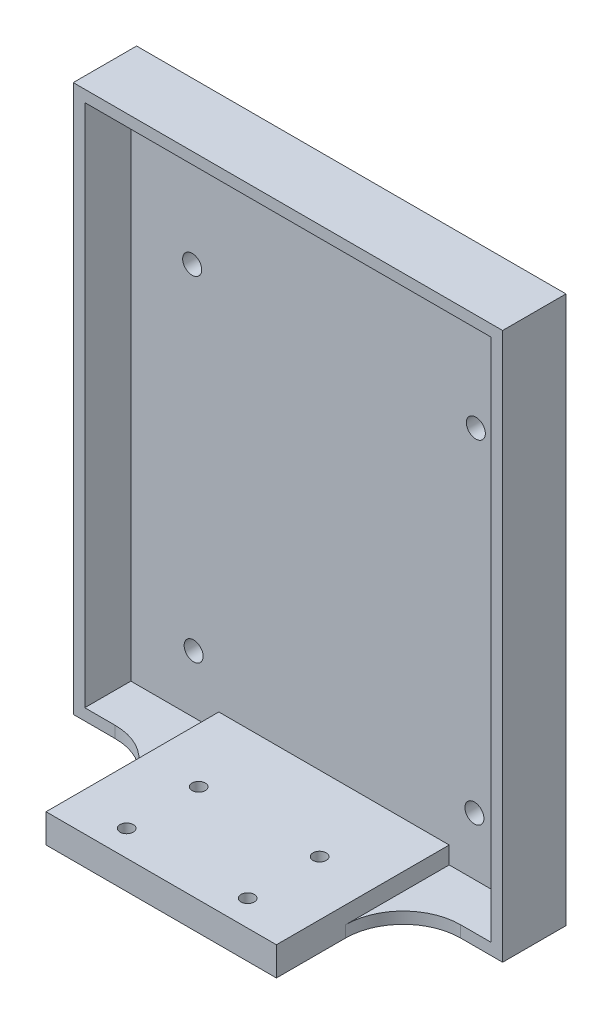
SolidWorks part; units mm, degrees
ref_plane "Alzado" through (0, 0, 0) normal (0, 0, 1) x (1, 0, 0)
ref_plane "Planta" through (0, 0, 0) normal (0, 1, 0) x (1, 0, 0)
ref_plane "Vista lateral" through (0, 0, 0) normal (1, 0, 0) x (0, 0, -1)
sketch "Croquis1" plane through (0, 0, 0) normal (0, 0, 1) x (1, 0, 0)
  line L0 (-55.75, 30) -> (-32.25, 30)
  line L1 (-32.25, 30) -> (-32.25, -30)
  line L2 (-32.25, -30) -> (-55, -34.2202)
  line L3 (-55, -34.2202) -> (-55, -125.7202)
  line L4 (-40.7501, 45) -> (0, 45)
  line L6 (-15, 15) -> (-15, -15)
  line L11 (-55, -125.7202) -> (-37.2737, -140.5944)
  line L12 (40.75, 45) -> (0, 45)
  line L17 (55, -125.7202) -> (37.2737, -140.5944)
  line L20 (15, 15) -> (15, -15)
  line L21 (-55, -79.9702) -> (55, -79.9702) construction
  line L22 (55, -34.2202) -> (55, -125.7202)
  line L23 (32.25, -30) -> (55, -34.2202)
  line L24 (32.25, 30) -> (32.25, -30)
  line L25 (55.75, 30) -> (32.25, 30)
  line L26 (-55.75, -189.9405) -> (-37.2737, -189.9405)
  line L27 (55.75, -189.9405) -> (37.2737, -189.9405)
  line L28 (40.75, -204.9405) -> (0, -204.9405)
  line L29 (-40.7501, -204.9405) -> (0, -204.9405)
  line L30 (-37.2737, -189.9405) -> (-37.2737, -140.5944)
  line L31 (37.2737, -189.9405) -> (37.2737, -140.5944)
  line L32 (-15, 15) -> (15, 15)
  line L33 (-15, -15) -> (15, -15)
  arc A4 (-55.75, 30) -> (-40.7501, 45) centre (-40.75, 30) cw
  arc A5 (55.75, 30) -> (40.75, 45) centre (40.75, 30) ccw
  arc A8 (55.75, -189.9405) -> (40.75, -204.9405) centre (40.75, -189.9405) cw
  arc A9 (-55.75, -189.9405) -> (-40.7501, -204.9405) centre (-40.75, -189.9405) ccw
  point P11 (0, 15)
  point P13 (-15, 0)
  point P20 (-32.25, 0)
  dimension "D10" = 15
  dimension "D22" = 15
  dimension "D1" = 60
  dimension "D3" = 55
  dimension "D4" = 23.5
  dimension "D5" = 91.5
  dimension "D6" = 23.1381
  dimension "D7" = 30
  dimension "D8" = 30
  dimension "D9" = 17.25
  dimension "D11" = 14.9999
  dimension "D12" = 15
  dimension "D13" = 23.14
  dimension "D14" = 18.4763
  dimension "D16" = 130
  dimension "D19" = 15
  dimension "D20" = 110
  dimension "D21" = 23.14
  dimension "D23" = 23.5
  dimension "D24" = 23.1381
extrude "Saliente-Extruir1" add sketch "Croquis1" along normal blind 15
sketch "Croquis6" plane through (-32.25, 0, 0) normal (-1, 0, 0) x (0, 0, 1)
  line L5 (0, 0) -> (5.215, 0) construction
  line L6 (0, 30) -> (0, -30) construction
  circle A0 centre (3, 0) radius 11.175
  circle A1 centre (3, 0) radius 5 construction
  circle A2 centre (3, 0) radius 25 construction
  dimension "D1" = 22.35
  dimension "D3" = 10
  dimension "D4" = 50
  dimension "D2" = 3
extrude "Cortar-Extruir1" cut sketch "Croquis6" against normal blind 10
sketch "Croquis11" plane through (0, 0, 0) normal (0, 0, -1) x (-1, 0, 0)
  line L0 (32.25, -10.7648) -> (32.25, -30) construction
  line L1 (15, 20) -> (32.25, 20)
  line L2 (15, 20) -> (15, -20)
  line L3 (15, -20) -> (32.25, -20)
  line L4 (32.25, 20) -> (32.25, -20)
  line L5 (15, 15) -> (15, -15) construction
  line L6 (55.75, 30) -> (32.25, 30) construction
  line L7 (0, -8.0419) -> (0, 11.3864) construction
  line L8 (-15, -20) -> (-32.25, -20)
  line L9 (-32.25, 20) -> (-32.25, -20)
  line L10 (-15, 20) -> (-32.25, 20)
  line L11 (-15, 20) -> (-15, -20)
  dimension "D1" = 10
  dimension "D2" = 10
extrude "Saliente-Extruir3" add sketch "Croquis11" along normal blind 12
sketch "Croquis9" plane through (-22.25, 0, 0) normal (-1, 0, 0) x (0, 0, 1)
  circle A0 centre (3, 0) radius 5
  arc A1 (0, -10.7648) -> (0, 10.7648) centre (3, 0) ccw construction
  dimension "D1" = 10
extrude "Cortar-Extruir2" cut sketch "Croquis9" against normal through all both and the other way through all
sketch "Croquis12" plane through (32.25, 0, 0) normal (1, 0, 0) x (0, 0, -1)
  line L2 (0, 0) -> (-9.4705, 0) construction
  line L5 (12, 20) -> (12, -20) construction
  line L6 (0, 20) -> (12, 20)
  line L7 (12, 20) -> (12, 5)
  line L8 (12, -20) -> (12, -5)
  line L9 (0, -20) -> (12, -20)
  arc A3 (12, 5) -> (0, 20) centre (-3.375, 5) ccw
  arc A4 (12, -5) -> (0, -20) centre (-3.375, -5) cw
  dimension "D1" = 15
sketch "Croquis14" plane through (0, 0, 15) normal (0, 0, 1) x (1, 0, 0)
  line L0 (-32.25, 30) -> (-32.25, -30) construction
  line L1 (32.25, 41.5932) -> (-32.25, 41.5932)
  line L2 (32.25, 41.5932) -> (32.25, -40.4068)
  line L3 (32.25, -40.4068) -> (-32.25, -40.4068)
  line L4 (-32.25, 41.5932) -> (-32.25, -40.4068)
  line L5 (32.25, -30) -> (32.25, 30) construction
  line L8 (40.75, 45) -> (-40.7501, 45) construction
  dimension "D1" = 3.4068
  dimension "D2" = 10.4068
extrude "Saliente-Extruir4" add sketch "Croquis14" along normal blind 40
sketch "Croquis10" plane through (32.25, 0, 0) normal (1, 0, 0) x (0, 0, -1)
  circle A0 centre (-3, 0) radius 11.175
  circle A1 centre (-3, 0) radius 5 construction
  arc A2 (0, 10.7648) -> (0, -10.7648) centre (-3, 0) ccw construction
extrude "Cortar-Extruir3" cut sketch "Croquis10" against normal blind 10
sketch "Croquis13" plane through (-32.25, 0, 0) normal (-1, 0, 0) x (0, 0, 1)
  circle A0 centre (3, 0) radius 11.175
  arc A1 (0, -10.7648) -> (0, 10.7648) centre (3, 0) ccw construction
extrude "Cortar-Extruir5" cut sketch "Croquis13" against normal blind 10 and the other way through all
sketch "Croquis15" plane through (0, -40.4068, 0) normal (0, -1, 0) x (1, 0, 0)
  line L0 (-22.25, 15) -> (-22.25, 35)
  line L1 (-32.25, 15) -> (32.25, 15) construction
  line L2 (-12.25, 45) -> (12.25, 45)
  line L3 (22.25, 35) -> (22.25, 15)
  line L4 (22.25, 15) -> (-22.25, 15)
  line L5 (-32.25, 55) -> (-32.25, 15) construction
  line L6 (32.25, 55) -> (32.25, 15) construction
  line L7 (-32.25, 55) -> (32.25, 55) construction
  arc A0 (22.25, 35) -> (12.25, 45) centre (12.25, 35) ccw
  arc A1 (-22.25, 35) -> (-12.25, 45) centre (-12.25, 35) cw
  dimension "D4" = 10
  dimension "D1" = 10
  dimension "D2" = 10
  dimension "D3" = 10
extrude "Cortar-Extruir6" cut sketch "Croquis15" against normal through all
sketch "Croquis16" plane through (0, 0, 55) normal (0, 0, 1) x (1, 0, 0)
  line L1 (-28, 38.5) -> (28, 38.5)
  line L2 (-28, 38.5) -> (-28, -38.5)
  line L3 (-28, -38.5) -> (28, -38.5)
  line L4 (28, 38.5) -> (28, -38.5)
  line L5 (-32.25, 41.5932) -> (32.25, 41.5932)
  line L6 (-32.25, 41.5932) -> (-32.25, -40.4068)
  line L7 (-32.25, -40.4068) -> (32.25, -40.4068)
  line L8 (32.25, 41.5932) -> (32.25, -40.4068)
  point P4 (0, 38.5)
  point P6 (28, 0)
  dimension "D1" = 77
  dimension "D2" = 56
extrude "Saliente-Extruir5" add sketch "Croquis16" along normal blind 5
sketch "Croquis17" plane through (0, 0, 15) normal (0, 0, 1) x (1, 0, 0)
  line L0 (15, 15) -> (15, 45)
  line L1 (15, 45) -> (-15, 45)
  line L2 (40.75, 45) -> (-40.7501, 45) construction
  line L3 (-15, 45) -> (-15, 15)
  line L4 (15, 15) -> (-15, 15) construction
  line L5 (15, 15) -> (-15, 15)
  line L6 (-15, 15) -> (-15, -15) construction
extrude "Cortar-Extruir7" cut sketch "Croquis17" against normal through all
sketch "Croquis19" plane through (0, -15, 0) normal (0, 1, 0) x (1, 0, 0)
  line L0 (-15, -15) -> (-15, 0) construction
  line L1 (15, -15) -> (-3, -15)
  line L2 (15, -15) -> (15, -10.5)
  line L3 (15, -10.5) -> (-3, -10.5)
  line L4 (-3, -15) -> (-3, -10.5)
  dimension "D1" = 12
  dimension "D2" = 2.5
extrude "Saliente-Extruir6" add sketch "Croquis19" along normal up to vertex (60 mm away)
sketch "Croquis22" plane through (0, -15, 0) normal (0, 1, 0) x (1, 0, 0)
  line L1 (-15, 0) -> (-3, 0)
  line L2 (-15, 0) -> (-15, -15)
  line L3 (-15, -15) -> (-3, -15)
  line L4 (-3, 0) -> (-3, -15)
extrude "Cortar-Extruir8" cut sketch "Croquis22" against normal blind 2
sketch "Croquis23" plane through (0, 0, 15) normal (0, 0, 1) x (1, 0, 0)
  line L1 (51.2, -56.4702) -> (55, -56.4702)
  line L2 (51.2, -56.4702) -> (51.2, -103.4702)
  line L3 (51.2, -103.4702) -> (55, -103.4702)
  line L4 (55, -56.4702) -> (55, -103.4702)
  line L6 (55, -125.7202) -> (55, -34.2202) construction
  line L7 (0, 0) -> (0, -130.3454) construction
  line L8 (-51.2, -103.4702) -> (-55, -103.4702)
  line L9 (-55, -56.4702) -> (-55, -103.4702)
  line L10 (-51.2, -56.4702) -> (-55, -56.4702)
  line L11 (-51.2, -56.4702) -> (-51.2, -103.4702)
  point P6 (55, -79.9702)
  point P7 (55, -79.9702)
  dimension "D1" = 3.8
  dimension "D2" = 47
extrude "Saliente-Extruir8" add sketch "Croquis23" along normal blind 19.8
sketch "Croquis24" plane through (55, 0, 0) normal (1, 0, 0) x (0, 0, -1)
  line L0 (-34.8, -103.4702) -> (-15, -103.4702) construction
  line L1 (-34.8, -103.4702) -> (-34.8, -56.4702) construction
  line L2 (-34.8, -102.4702) -> (-15, -102.4702) construction
  line L3 (-34.8, -102.4702) -> (-34.8, -57.4702) construction
  line L4 (-34.8, -57.4702) -> (-15, -57.4702) construction
  line L5 (-15, -102.4702) -> (-15, -57.4702) construction
  line L6 (-15, -125.7202) -> (-15, -103.4702) construction
  line L7 (-34.8, -56.4702) -> (-15, -56.4702) construction
  line L8 (-20.1, -85.9702) -> (-15.3, -85.9702)
  line L9 (-20.1, -85.9702) -> (-20.1, -73.9702)
  line L10 (-20.1, -73.9702) -> (-15.3, -73.9702)
  line L11 (-15.3, -85.9702) -> (-15.3, -73.9702)
  line L12 (-24.9, -56.4702) -> (-24.9, -58.3702) construction
  line L13 (-24.9, -103.4702) -> (-24.9, -101.771) construction
  circle A0 centre (-25.3, -66.9702) radius 8.35
  circle A1 centre (-25.3, -92.9702) radius 8.35
  circle A2 centre (-16.3, -101.2702) radius 1
  circle A3 centre (-33.7, -58.3702) radius 1
  circle A4 centre (-16.1, -58.3702) radius 1
  circle A5 centre (-33.5, -101.2702) radius 1
  point P16 (-20.1, -79.9702)
  point P20 (-34.8, -79.9702)
  point P21 (-34.8, -79.9702)
  dimension "D1" = 16.7
  dimension "D2" = 16.7
  dimension "D3" = 2
  dimension "D4" = 2.2
  dimension "D5" = 2
  dimension "D6" = 1.9
  dimension "D7" = 45
  dimension "D8" = 13
  dimension "D9" = 1.3
  dimension "D10" = 1.1
  dimension "D11" = 13
  dimension "D12" = 12
  dimension "D13" = 4.8
  dimension "D14" = 0.3
  dimension "D15" = 9.5
extrude "Cortar-Extruir10" cut sketch "Croquis24" against normal through all
sketch "Croquis25" plane through (0, 0, 34.8) normal (0, 0, 1) x (1, 0, 0)
  line L1 (-55, -56.4702) -> (-51.2, -56.4702)
  line L2 (-55, -56.4702) -> (-55, -103.4702)
  line L3 (-55, -103.4702) -> (-51.2, -103.4702)
  line L4 (-51.2, -56.4702) -> (-51.2, -103.4702)
  line L5 (51.2, -56.4702) -> (55, -56.4702)
  line L6 (51.2, -56.4702) -> (51.2, -103.4702)
  line L7 (51.2, -103.4702) -> (55, -103.4702)
  line L8 (55, -56.4702) -> (55, -103.4702)
extrude "Saliente-Extruir9" add sketch "Croquis25" along normal blind 2
fillet "Redondeo2" radius 3 4 edges at (53.1, -56.4702, 36.8) (53.1, -103.4702, 36.8) (-53.1, -56.4702, 36.8) (-53.1, -103.4702, 36.8)
sketch "Croquis26" plane through (0, 0, 15) normal (0, 0, 1) x (1, 0, 0)
  line L0 (-23.5001, -201.1405) -> (-23.5001, -204.9405)
  line L1 (-23.5001, -204.9405) -> (23.4999, -204.9405)
  line L2 (23.4999, -204.9405) -> (23.4999, -201.1405)
  line L3 (23.4999, -201.1405) -> (-23.5001, -201.1405)
  line L4 (-40.7501, -204.9405) -> (40.75, -204.9405) construction
  point P6 (-0.0001, -204.9405)
  point P7 (-0.0001, -204.9405)
  dimension "D1" = 3.8
  dimension "D2" = 47
extrude "Saliente-Extruir10" add sketch "Croquis26" along normal blind 21.8
fillet "Redondeo3" radius 3 2 edges at (23.4999, -203.0405, 36.8) (-23.5001, -203.0405, 36.8)
sketch "Croquis28" plane through (0, -204.9405, 0) normal (0, -1, 0) x (1, 0, 0)
  line L0 (-32.25, 15) -> (-22.25, 15) construction
  line L1 (-6, 20.1) -> (6, 20.1)
  line L2 (-6, 20.1) -> (-6, 15.3)
  line L3 (-6, 15.3) -> (6, 15.3)
  line L4 (6, 20.1) -> (6, 15.3)
  line L5 (-20.5001, 36.8) -> (20.4999, 36.8) construction
  line L6 (-23.5001, 33.8) -> (-23.5001, 15) construction
  line L8 (23.4999, 33.8) -> (23.4999, 15) construction
  line L9 (0, -0.6164) -> (0, 0) construction
  line L10 (0, 0) -> (0, -5.7529) construction
  circle A0 centre (-13, 25.3) radius 8.35
  circle A1 centre (13, 25.3) radius 8.35
  circle A2 centre (-21.3001, 16.3) radius 1
  circle A3 centre (21.5999, 33.7) radius 1
  circle A4 centre (21.3001, 16.3) radius 1
  circle A5 centre (-21.5999, 33.7) radius 1
  point P6 (0, 15.3)
  dimension "D4" = 16.7
  dimension "D7" = 16.7
  dimension "D9" = 2
  dimension "D12" = 2
  dimension "D1" = 0.3
  dimension "D2" = 12
  dimension "D3" = 4.8
  dimension "D5" = 13
  dimension "D6" = 13
  dimension "D8" = 11.5
  dimension "D10" = 2.2
  dimension "D11" = 1.3
  dimension "D13" = 1.9
  dimension "D14" = 3.1
extrude "Cortar-Extruir11" cut sketch "Croquis28" against normal blind 21.8
extrude "Cortar-Extruir12" cut sketch "Croquis12" against normal through all both and the other way through all
sketch "Croquis29" plane through (0, 0, 15) normal (0, 0, 1) x (1, 0, 0)
  line L2 (0, 0) -> (0, -45.8702) construction
  circle A0 centre (-24.3737, -132.9944) radius 1.65
  circle A1 centre (24.6263, -74.9944) radius 1.65
  circle A2 centre (-24.6263, -74.9944) radius 1.65
  circle A3 centre (24.3737, -132.9944) radius 1.65
  dimension "D1" = 3.3
  dimension "D3" = 12.9
  dimension "D4" = 3.3
  dimension "D2" = 7.6
  dimension "D5" = 58
  dimension "D6" = 49
extrude "Cortar-Extruir13" cut sketch "Croquis29" against normal through all both and the other way through all
sketch "Croquis32" plane through (0, 0, 0) normal (0, 0, -1) x (-1, 0, 0)
  line L0 (0, 0) -> (0, -47.6418) construction
  circle A0 centre (-24.6263, -74.9944) radius 5.15
  circle A1 centre (-24.6263, -74.9944) radius 1.65 construction
  circle A2 centre (-24.3737, -132.9944) radius 5.15
  circle A3 centre (-24.3737, -132.9944) radius 1.65 construction
  circle A4 centre (24.3737, -132.9944) radius 5.15
  circle A5 centre (24.6263, -74.9944) radius 5.15
  dimension "D1" = 3.5
  dimension "D2" = 3.5
extrude "Cortar-Extruir14" cut sketch "Croquis32" against normal blind 8 and the other way through all
sketch "Croquis34" plane through (0, 0, 0) normal (0, 0, -1) x (-1, 0, 0)
  line L0 (-37.2737, -189.9405) -> (-37.2737, -140.5944) construction
  line L1 (-37.2737, -140.5944) -> (-15, -140.5944)
  line L2 (-37.2737, -140.5944) -> (-37.2737, -189.9405)
  line L3 (-37.2737, -189.9405) -> (-15, -189.9405)
  line L4 (-15, -140.5944) -> (-15, -189.9405)
  line L5 (-15, 45) -> (-15, 20) construction
  line L6 (15, -140.5944) -> (37.2737, -140.5944)
  line L7 (15, -140.5944) -> (15, -189.9405)
  line L8 (15, -189.9405) -> (37.2737, -189.9405)
  line L9 (37.2737, -140.5944) -> (37.2737, -189.9405)
  line L10 (37.2737, -140.5944) -> (37.2737, -189.9405) construction
  line L11 (15, 20) -> (15, 45) construction
extrude "Saliente-Extruir11" add sketch "Croquis34" along normal blind 12
sketch "Croquis35" plane through (37.2737, 0, 0) normal (1, 0, 0) x (0, 0, -1)
  line L0 (0, -140.5944) -> (12, -140.5944)
  line L1 (12, -140.5944) -> (12, -148.5944)
  line L3 (0, -189.9405) -> (12, -189.9405)
  line L4 (12, -189.9405) -> (12, -181.9405)
  line L5 (12, -140.5944) -> (12, -189.9405) construction
  arc A3 (0, -189.9405) -> (12, -181.9405) centre (-7.782, -165.2674) ccw
  arc A4 (12, -148.5944) -> (0, -140.5944) centre (-7.782, -165.2674) ccw
  dimension "D1" = 8
extrude "Cortar-Extruir17" cut sketch "Croquis35" against normal through all both and the other way through all
sketch "Croquis37" plane through (-37.2737, 0, 0) normal (-1, 0, 0) x (0, 0, 1)
  line L0 (-12, -181.9405) -> (-12, -148.5944) construction
  line L1 (0, -140.5944) -> (0, -189.9405) construction
  line L7 (-4.5, -155.2674) -> (10.5, -155.2674)
  line L8 (-4.5, -155.2674) -> (-4.5, -181.2674)
  line L9 (-0.5, -185.2674) -> (6.5, -185.2674)
  line L10 (10.5, -155.2674) -> (10.5, -181.2674)
  circle A0 centre (3, -165.2674) radius 5.5 construction
  arc A1 (6.5, -185.2674) -> (10.5, -181.2674) centre (6.5, -181.2674) ccw
  arc A2 (-0.5, -185.2674) -> (-4.5, -181.2674) centre (-0.5, -181.2674) cw
  point P5 (-12, -165.2674)
  point P14 (3, -185.2674)
  point P16 (10.5, -185.2674)
  point P19 (-4.5, -185.2674)
  dimension "D1" = 11
  dimension "D4" = 30
  dimension "D6" = 4
  dimension "D2" = 3
  dimension "D3" = 10
  dimension "D5" = 15
extrude "Cortar-Extruir18" cut sketch "Croquis37" against normal through all both and the other way through all
sketch "Croquis38" plane through (0, 0, -12) normal (0, 0, -1) x (-1, 0, 0)
  line L0 (-37.2737, -148.5944) -> (-37.2737, -181.9405) construction
  line L1 (-15, -148.5944) -> (-37.2737, -148.5944) construction
  line L2 (0, 0) -> (0, -210.3255) construction
  circle A0 centre (-26.1369, -165.2674) radius 1.3
  circle A1 centre (26.1369, -165.2674) radius 1.3
  point P5 (-37.2737, -165.2674)
  point P9 (-26.1369, -148.5944)
  dimension "D1" = 2.6
extrude "Cortar-Extruir19" cut sketch "Croquis38" against normal through all both and the other way through all
sketch "Croquis39" plane through (0, 0, 15) normal (0, 0, 1) x (1, 0, 0)
  line L0 (37.2737, -189.9405) -> (37.2737, -140.5944) construction
  line L1 (-37.2737, -185.2674) -> (37.2737, -185.2674)
  line L2 (-37.2737, -185.2674) -> (-37.2737, -174.2674)
  line L3 (-37.2737, -174.2674) -> (37.2737, -174.2674)
  line L4 (37.2737, -185.2674) -> (37.2737, -174.2674)
  line L5 (-37.2737, -140.5944) -> (-37.2737, -189.9405) construction
  dimension "D1" = 11
extrude "Cortar-Extruir20" cut sketch "Croquis39" against normal up to vertex and the other way through all
sketch "Croquis40" plane through (0, 0, 15) normal (0, 0, 1) x (1, 0, 0)
  line L0 (-37.2737, -174.2674) -> (37.2737, -174.2674) construction
  line L1 (-8.5, -174.2674) -> (8.5, -174.2674)
  line L2 (-8.5, -174.2674) -> (-8.5, -152.2674)
  line L3 (-8.5, -152.2674) -> (8.5, -152.2674)
  line L4 (8.5, -174.2674) -> (8.5, -152.2674)
  point P6 (0, -174.2674)
  dimension "D1" = 22
  dimension "D2" = 17
extrude "Saliente-Extruir12" add sketch "Croquis40" along normal blind 15
sketch "Croquis41" plane through (0, 0, 30) normal (0, 0, 1) x (1, 0, 0)
  line L1 (8.5, -152.2674) -> (-8.5, -152.2674) construction
  circle A0 centre (0, -153.7674) radius 1.3
  dimension "D1" = 2.6
  dimension "D2" = 1.5
extrude "Cortar-Extruir25" cut sketch "Croquis41" against normal blind 15
sketch "Croquis42" plane through (0, 0, 30) normal (0, 0, 1) x (1, 0, 0)
  line L2 (-6.3, -157.2674) -> (6.3, -157.2674)
  line L3 (-6.3, -157.2674) -> (-6.3, -164.2674)
  line L4 (-6.3, -164.2674) -> (6.3, -164.2674)
  line L5 (6.3, -157.2674) -> (6.3, -164.2674)
  circle A0 centre (0, -153.7674) radius 1.3 construction
  point P0 (0, -157.2674)
  dimension "D1" = 12.6
  dimension "D2" = 3.5
  dimension "D3" = 7
extrude "Cortar-Extruir26" cut sketch "Croquis42" against normal blind 7.1
sketch "Croquis43" plane through (0, 0, 30) normal (0, 0, 1) x (1, 0, 0)
  line L0 (-8.5, -174.2674) -> (8.5, -174.2674) construction
  line L1 (-6.3, -164.2674) -> (6.3, -164.2674)
  line L2 (-6.3, -164.2674) -> (-6.3, -174.2674)
  line L3 (-6.3, -174.2674) -> (6.3, -174.2674)
  line L4 (6.3, -164.2674) -> (6.3, -174.2674)
  line L5 (6.3, -164.2674) -> (6.3, -157.2674) construction
extrude "Cortar-Extruir27" cut sketch "Croquis43" against normal blind 12.1
sketch "Croquis44" plane through (0, 0, 15) normal (0, 0, 1) x (1, 0, 0)
  line L0 (37.2737, -174.2674) -> (37.2737, -140.5944) construction
  line L1 (-37.2737, -49.9944) -> (37.2737, -49.9944)
  line L2 (-37.2737, -49.9944) -> (-37.2737, -144.9944)
  line L3 (-37.2737, -144.9944) -> (37.2737, -144.9944)
  line L4 (37.2737, -49.9944) -> (37.2737, -144.9944)
  line L5 (-37.2737, -140.5944) -> (-37.2737, -174.2674) construction
  line L6 (-75.3992, 56.8457) -> (81.771, 56.8457)
  line L7 (-75.3992, 56.8457) -> (-75.3992, -215.3702)
  line L8 (-75.3992, -215.3702) -> (81.771, -215.3702)
  line L9 (81.771, 56.8457) -> (81.771, -215.3702)
  circle A0 centre (-24.6263, -74.9944) radius 1.65 construction
  circle A1 centre (-24.3737, -132.9944) radius 1.65 construction
  dimension "D1" = 25
  dimension "D2" = 12
extrude "Cortar-Extruir28" cut sketch "Croquis44" against normal through all both and the other way through all
sketch "Croquis45" plane through (0, 0, 0) normal (0, 0, -1) x (-1, 0, 0)
  line L1 (-37.2737, -49.9944) -> (37.2737, -49.9944)
  line L2 (-37.2737, -49.9944) -> (-37.2737, -144.9944)
  line L3 (-37.2737, -144.9944) -> (37.2737, -144.9944)
  line L4 (37.2737, -49.9944) -> (37.2737, -144.9944)
extrude "Cortar-Extruir29" cut sketch "Croquis45" against normal blind 12 and the other way through all
sketch "Croquis46" plane through (0, 0, 15) normal (0, 0, 1) x (1, 0, 0)
  line L1 (-20, -139.9944) -> (20, -139.9944)
  line L2 (-20, -139.9944) -> (-20, -144.9944)
  line L3 (-20, -144.9944) -> (20, -144.9944)
  line L4 (20, -139.9944) -> (20, -144.9944)
  line L5 (37.2737, -144.9944) -> (-37.2737, -144.9944) construction
  line L6 (-37.2737, -49.9944) -> (37.2737, -49.9944) construction
  point P9 (0, -49.9944)
  point P10 (0, -144.9944)
  dimension "D1" = 5
  dimension "D2" = 40
extrude "Saliente-Extruir13" add sketch "Croquis46" along normal blind 30
sketch "Croquis47" plane through (0, 0, 15) normal (0, 0, 1) x (1, 0, 0)
  line L1 (-37.2737, -49.9944) -> (37.2737, -49.9944)
  line L2 (-37.2737, -49.9944) -> (-37.2737, -144.9944)
  line L3 (-37.2737, -144.9944) -> (37.2737, -144.9944)
  line L4 (37.2737, -49.9944) -> (37.2737, -144.9944)
  line L5 (-35.2737, -51.9944) -> (35.2737, -51.9944)
  line L6 (-35.2737, -51.9944) -> (-35.2737, -142.9944)
  line L7 (-35.2737, -142.9944) -> (35.2737, -142.9944)
  line L8 (35.2737, -51.9944) -> (35.2737, -142.9944)
  point P10 (0, -49.9944)
  point P11 (0, -51.9944)
  point P12 (-35.2737, -97.4944)
  point P13 (-37.2737, -97.4944)
  dimension "D1" = 2
  dimension "D2" = 2
extrude "Saliente-Extruir14" add sketch "Croquis47" along normal blind 8
fillet "Redondeo4" radius 10 2 edges at (-20, -143.9944, 23) (20, -143.9944, 23)
sketch "Croquis49" plane through (0, -144.9944, 0) normal (0, -1, 0) x (1, 0, 0)
  line L0 (-37.2737, 23) -> (-30, 23) construction
  line L1 (-10.5, 40.5) -> (10.5, 40.5) construction
  line L2 (-10.5, 40.5) -> (-10.5, 28) construction
  line L3 (-10.5, 28) -> (10.5, 28) construction
  line L4 (10.5, 40.5) -> (10.5, 28) construction
  circle A0 centre (-10.5, 40.5) radius 1.15
  circle A1 centre (10.5, 40.5) radius 1.15
  circle A2 centre (-10.5, 28) radius 1.15
  circle A3 centre (10.5, 28) radius 1.15
  point P8 (0, 40.5)
  dimension "D1" = 2.3
  dimension "D2" = 2.3
  dimension "D3" = 2.3
  dimension "D4" = 2.3
  dimension "D5" = 21
  dimension "D6" = 12.5
  dimension "D7" = 5
extrude "Cortar-Extruir30" cut sketch "Croquis49" against normal blind 8
